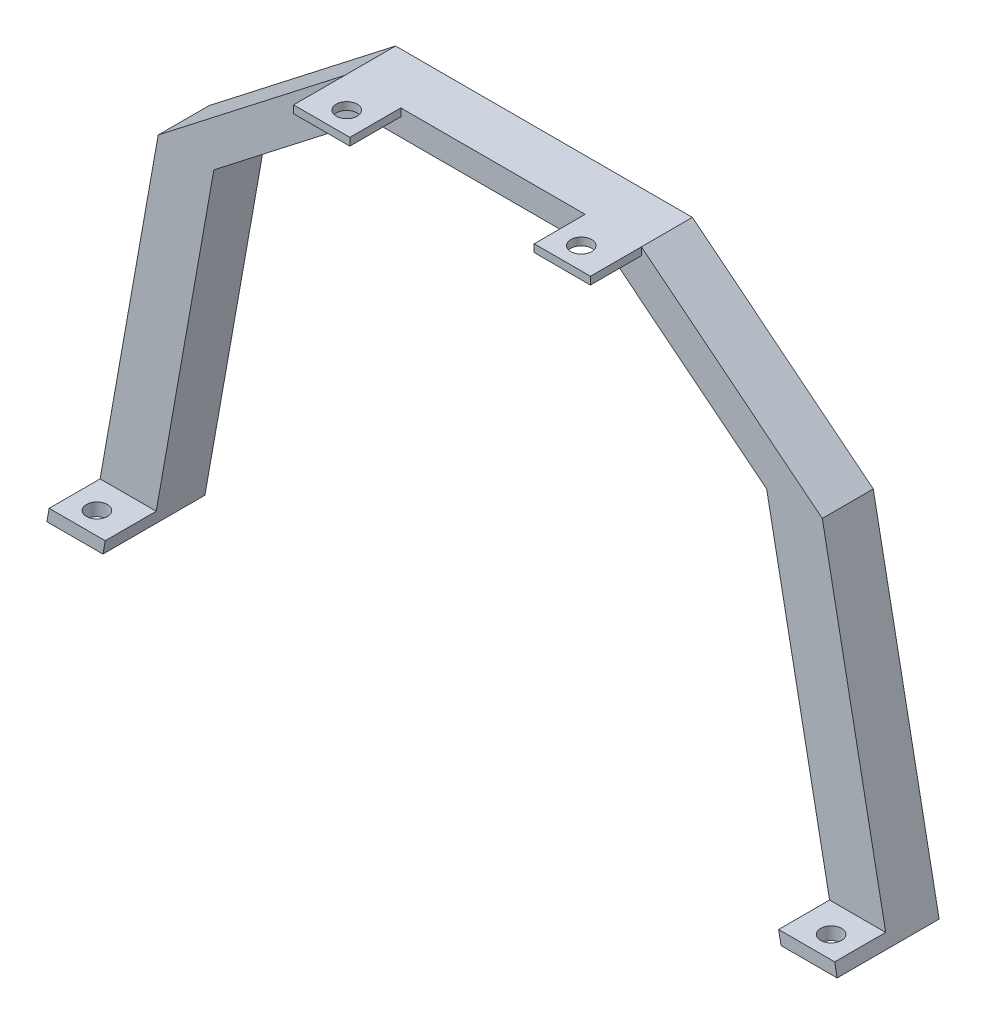
SolidWorks part; units mm, degrees
ref_plane "Front Plane" through (0, 0, 0) normal (0, 0, 1) x (1, 0, 0)
ref_plane "Top Plane" through (0, 0, 0) normal (0, 1, 0) x (1, 0, 0)
ref_plane "Right Plane" through (0, 0, 0) normal (1, 0, 0) x (0, 0, -1)
sketch "Sketch1" plane through (0, 0, 0) normal (0, 0, 1) x (1, 0, 0)
  line L0 (0, 0) -> (-11, 0)
  line L2 (133, 0) -> (144, 0)
  line L3 (-11, 0) -> (0.8295, 66.6053)
  line L16 (0.8295, 66.6053) -> (37.3909, 95)
  line L17 (37.3909, 95) -> (95.6091, 95)
  line L18 (95.6091, 95) -> (131.0841, 66.6053)
  line L19 (131.0841, 66.6053) -> (144, 0)
  line L20 (0, 0) -> (11.7454, 66.1314)
  line L21 (11.7454, 66.1314) -> (42.4789, 90)
  line L22 (42.4789, 90) -> (90.3556, 90)
  line L23 (90.3556, 90) -> (120.176, 66.1314)
  line L24 (120.176, 66.1314) -> (133, 0)
  point P1 (-2.9391, 62.456)
  point P3 (35.2693, 73.8859)
  point P7 (39.6779, 70)
  point P9 (127.5246, 60.4716)
  point P10 (118.0541, 60.4716)
  point P11 (131.8479, 62.8454)
  point P12 (130.3578, 64.6734)
  point P13 (120.5555, 113.0211)
  point P14 (2.6107, 90)
  point P15 (16.2275, 75.763)
  point P16 (0, 0)
  point P17 (0, 0)
  point P18 (0, 0)
  point P25 (0, 0)
  point P26 (66.5, 95)
  point P27 (0, 0)
  point P29 (110.0544, 92.138)
  point P30 (108.5713, 77.088)
  point P31 (39.8213, 90)
  point P32 (16.1353, 74.7916)
  point P33 (124.8226, 84.5119)
  point P34 (0, 58.0538)
  point P35 (35.0356, 95.8087)
  point P36 (35.5286, 90)
  point P37 (9.8422, 55.416)
  point P38 (28.4213, 96.6914)
  point P39 (119.2999, 58.0538)
  point P40 (128.6976, 66.6053)
  point P41 (102.764, 96.0438)
  point P42 (91.9854, 90)
  point P43 (119.8256, 64.1589)
  dimension "D1" = 155
  dimension "D2" = 11
  dimension "D3" = 90
  dimension "D4" = 77.5
  dimension "D5" = 5
extrude "Boss-Extrude1" add sketch "Sketch1" along normal blind 10
sketch "Sketch2" plane through (0, 0, 10) normal (0, 0, 1) x (1, 0, 0)
  line L0 (-11, 0) -> (0, 0)
  line L1 (0, 0) -> (0.444, 2.5)
  line L2 (0, 0) -> (11.7454, 66.1314) construction
  line L3 (0.444, 2.5) -> (-10.556, 2.5)
  line L4 (0.8295, 66.6053) -> (-11, 0) construction
  line L5 (-10.556, 2.5) -> (-11, 0)
  line L6 (133, 0) -> (144, 0)
  line L7 (144, 0) -> (143.5152, 2.5)
  line L8 (144, 0) -> (131.0841, 66.6053) construction
  line L9 (143.5152, 2.5) -> (132.5152, 2.5)
  line L10 (120.176, 66.1314) -> (133, 0) construction
  line L11 (132.5152, 2.5) -> (133, 0)
  dimension "D1" = 2.5
  dimension "D2" = 2.5
extrude "Boss-Extrude2" add sketch "Sketch2" along normal blind 10
sketch "Sketch3" plane through (0, 2.5, 0) normal (0, 1, 0) x (1, 0, 0)
  line L0 (-11, -20) -> (-11, 0) construction
  line L1 (144, -20) -> (144, 0) construction
  circle A0 centre (-5.5, -15.6874) radius 2.05
  circle A1 centre (138.5, -15.6874) radius 2.05
  dimension "D3" = 4.1
  dimension "D1" = 5.5
  dimension "D2" = 5.5
extrude "Cut-Extrude1" cut sketch "Sketch3" against normal blind 10
sketch "Sketch4" plane through (0, 0, 10) normal (0, 0, 1) x (1, 0, 0)
  line L0 (-11, 0) -> (66.5, 0)
  line L1 (37.3909, 95) -> (48.4211, 95)
  line L2 (37.3909, 95) -> (37.3909, 93.5)
  line L3 (37.3909, 93.5) -> (48.4211, 93.5)
  line L4 (48.4211, 95) -> (48.4211, 93.5)
  line L9 (66.5, 0) -> (66.5, 79.0988)
  line L10 (84.5789, 95) -> (84.5789, 93.5)
  line L11 (95.6091, 93.5) -> (84.5789, 93.5)
  line L12 (95.6091, 95) -> (95.6091, 93.5)
  line L13 (95.6091, 95) -> (84.5789, 95)
  dimension "D1" = 155
  dimension "D2" = 77.5
  dimension "D3" = 1.5
extrude "Boss-Extrude3" add sketch "Sketch4" along normal blind 10 contours L3 L4 L1 L2 | L13 L10 L11 L12
sketch "Sketch6" plane through (0, 95, 0) normal (0, 1, 0) x (1, 0, 0)
  line L3 (66.5, -10) -> (66.5, 0)
  line L4 (84.5789, -10) -> (48.4211, -10) construction
  line L5 (95.6091, 0) -> (37.3909, 0) construction
  circle A0 centre (43.5, -15.6874) radius 2.05
  circle A1 centre (89.5, -15.6874) radius 2.05
  circle A7 centre (-5.5, -15.6874) radius 2.05
  point P2 (0, 0)
  dimension "D2" = 4.1
  dimension "D1" = 23
extrude "Cut-Extrude2" cut sketch "Sketch6" against normal blind 10 contours A0 | A1
